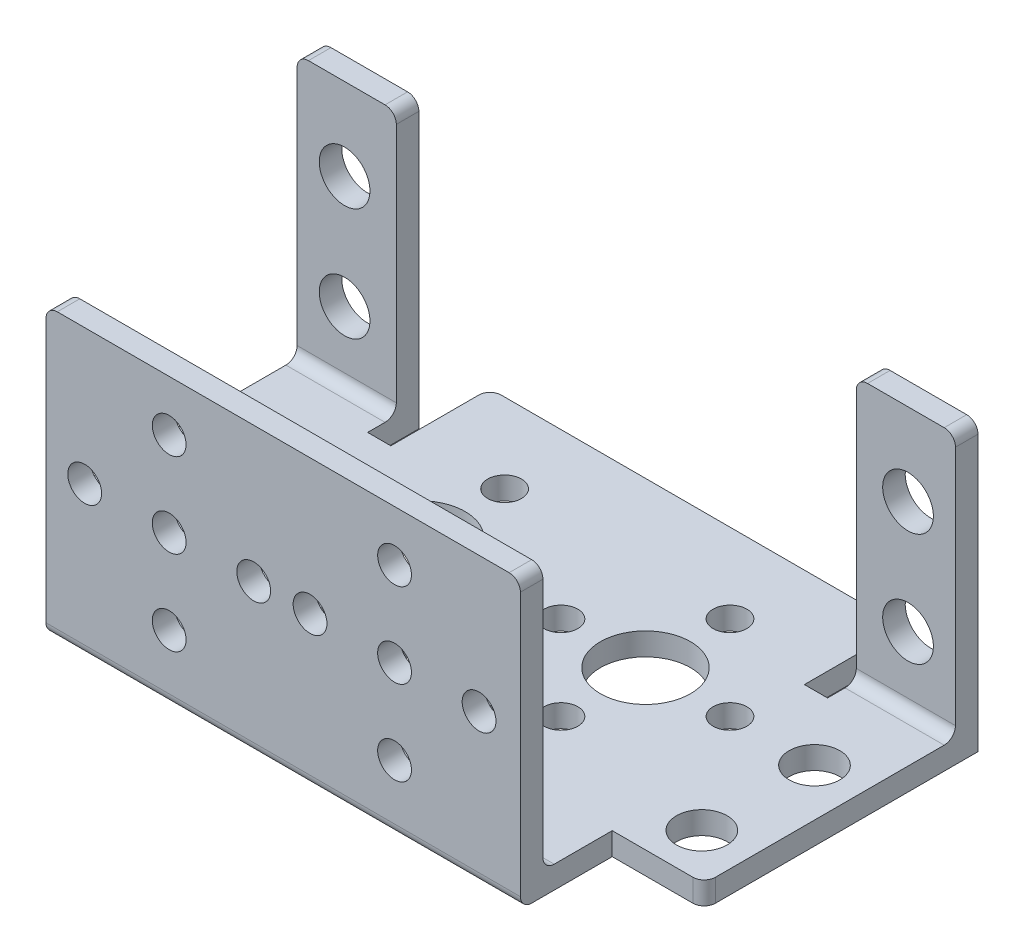
SolidWorks part; units mm, degrees
material "1060 Alloy"
ref_plane "Front Plane" through (0, 0, 0) normal (0, 0, 1) x (1, 0, 0)
ref_plane "Top Plane" through (0, 0, 0) normal (0, 1, 0) x (1, 0, 0)
ref_plane "Right Plane" through (0, 0, 0) normal (1, 0, 0) x (0, 0, -1)
sketch "Sketch2" plane through (0, 0, 0) normal (0, 0, 1) x (1, 0, 0)
  line L1 (0, 0) -> (58.42, 0)
  line L2 (0, 0) -> (0, 25.4)
  line L3 (0, 25.4) -> (58.42, 25.4)
  line L4 (58.42, 0) -> (58.42, 25.4)
  dimension "D1" = 25.4
  dimension "D2" = 58.42
extrude "Boss-Extrude1" add sketch "Sketch2" along normal blind 36.7
sketch "Sketch3" plane through (58.42, 0, 0) normal (1, 0, 0) x (0, 0, -1)
  line L0 (-36.7, 25.4) -> (0, 25.4) construction
  line L1 (-34.7, 25.4) -> (-6.252, 25.4)
  line L2 (-34.7, 25.4) -> (-34.7, 2)
  line L3 (-34.7, 2) -> (-6.252, 2)
  line L4 (-6.252, 25.4) -> (-6.252, 2)
  line L5 (-36.7, 0) -> (-36.7, 25.4) construction
  line L6 (-36.7, 0) -> (0, 0) construction
  line L7 (-4.252, 25.4) -> (-4.252, 2)
  line L8 (-4.252, 2) -> (0, 2)
  line L9 (0, 0) -> (0, 25.4) construction
  line L10 (-6.252, 25.4) -> (-4.252, 25.4)
  line M1 (0, 0) -> (0, 25.4)
  line M2 (0, 25.4) -> (-36.7, 25.4)
  dimension "D1" = 2
  dimension "D2" = 2
  dimension "D3" = 28.448
  dimension "D4" = 2
extrude "Cut-Extrude1" cut sketch "Sketch3" against normal up to next contours L7 L8 M1 M2 | L4 L2 L3 M2
sketch "Sketch4" plane through (0, 0, 36.7) normal (0, 0, 1) x (1, 0, 0)
  line L0 (0, 25.4) -> (58.42, 0) construction
  line L1 (58.42, 25.4) -> (0, 0) construction
  line L2 (58.42, 25.4) -> (0, 25.4) construction
  line L3 (50.26, 0) -> (8.16, 0)
  line L4 (50.26, 0) -> (50.26, 25.4)
  line L5 (50.26, 25.4) -> (8.16, 25.4)
  line L6 (8.16, 0) -> (8.16, 25.4)
  line L7 (50.26, 0) -> (8.16, 25.4) construction
  line L8 (50.26, 25.4) -> (8.16, 0) construction
  line L9 (0, 2) -> (58.42, 2)
  line L10 (8.16, 25.4) -> (0, 25.4)
  line L11 (8.16, 25.4) -> (8.16, 0)
  line L12 (8.16, 0) -> (0, 0)
  line L13 (0, 25.4) -> (0, 0)
  line L14 (50.26, 25.4) -> (58.42, 25.4)
  line L15 (50.26, 25.4) -> (50.26, 0)
  line L16 (50.26, 0) -> (58.42, 0)
  line L17 (58.42, 25.4) -> (58.42, 0)
  point P8 (29.21, 12.7)
  line M5 (0, 25.4) -> (0, 0)
  line M7 (58.42, 0) -> (58.42, 25.4)
  line M8 (58.42, 25.4) -> (0, 25.4)
  dimension "D1" = 42.1
  dimension "D2" = 2
extrude "Cut-Extrude3" cut sketch "Sketch4" against normal blind 2 contours L9 L6 M5 M8 | L4 L9 M7 M8
fillet "Fillet1" radius 1 4 edges at (29.21, 0, 36.7) (8.16, 25.4, 35.7) (50.26, 25.4, 35.7) (29.21, 2, 34.7)
sketch "Sketch5" plane through (0, 0, 4.252) normal (0, 0, -1) x (-1, 0, 0)
  line L0 (0, 2) -> (-58.42, 2) construction
  line L1 (-58.42, 25.4) -> (-49.62, 25.4)
  line L2 (-58.42, 25.4) -> (-58.42, 2)
  line L3 (-58.42, 2) -> (-49.62, 2)
  line L4 (-49.62, 25.4) -> (-49.62, 2)
  line L5 (0, 25.4) -> (-58.42, 25.4) construction
  line L6 (0, 25.4) -> (-8.8, 25.4)
  line L7 (0, 25.4) -> (0, 2)
  line L8 (0, 2) -> (-8.8, 2)
  line L9 (-8.8, 25.4) -> (-8.8, 2)
  line L10 (0, 2) -> (0, 25.4) construction
  line L12 (-49.62, 25.4) -> (-8.8, 25.4)
  line L13 (-49.62, 25.4) -> (-49.62, 2)
  line L14 (-49.62, 2) -> (-8.8, 2)
  line L15 (-8.8, 25.4) -> (-8.8, 2)
  line M2 (0, 25.4) -> (-58.42, 25.4)
  line M4 (-58.42, 2) -> (0, 2)
  dimension "D1" = 8.8
  dimension "D2" = 8.8
extrude "Cut-Extrude5" cut sketch "Sketch5" against normal up to next contours L9 L4 M2 M4
sketch "Sketch6" plane through (0, 2, 0) normal (0, 1, 0) x (1, 0, 0)
  line L0 (0, 0) -> (58.42, 0) construction
  line L1 (47.56, 0) -> (10.86, 0)
  line L2 (47.56, 0) -> (47.56, -8.8)
  line L3 (47.56, -8.8) -> (10.86, -8.8)
  line L4 (10.86, 0) -> (10.86, -8.8)
  line L5 (0, 0) -> (58.42, -36.7) construction
  line L6 (58.42, -36.7) -> (0, -36.7) construction
  line L7 (0, -36.7) -> (58.42, 0) construction
  line L8 (29.21, -33.7) -> (29.21, 0) construction
  line L9 (8.16, -33.7) -> (50.26, -33.7) construction
  line L10 (47.56, -4.4) -> (10.86, -4.4) construction
  line L11 (29.21, -8.8) -> (29.21, 0) construction
  line L12 (10.86, 0) -> (0, 0)
  line L13 (49.62, -6.252) -> (47.56, -6.252)
  line L14 (49.62, -6.252) -> (49.62, -8.8)
  line L15 (49.62, -8.8) -> (47.56, -8.8)
  line L16 (47.56, -6.252) -> (47.56, -8.8)
  line L17 (8.8, -6.252) -> (10.86, -6.252)
  line L18 (8.8, -6.252) -> (8.8, -8.8)
  line L19 (8.8, -8.8) -> (10.86, -8.8)
  line L20 (10.86, -6.252) -> (10.86, -8.8)
  line L21 (0, 0) -> (0, -4.252)
  line L22 (0, -4.252) -> (8.8, -4.252)
  line L23 (8.8, -4.252) -> (8.8, -6.252)
  line L24 (47.56, 0) -> (58.42, 0)
  line L25 (58.42, 0) -> (58.42, -4.252)
  line L26 (58.42, -4.252) -> (49.62, -4.252)
  line L27 (49.62, -4.252) -> (58.42, -4.252) construction
  line L28 (49.62, -4.252) -> (49.62, -6.252)
  line M1 (0, 0) -> (0, -4.252)
  line M2 (0, -4.252) -> (8.8, -4.252)
  line M3 (8.8, -4.252) -> (8.8, -6.252)
  line M13 (49.62, -6.252) -> (49.62, -4.252)
  line M14 (49.62, -4.252) -> (58.42, -4.252)
  line M15 (58.42, -4.252) -> (58.42, 0)
  line M16 (58.42, 0) -> (0, 0)
  dimension "D1" = 8.8
  dimension "D2" = 36.7
  dimension "D3" = 0
extrude "Cut-Extrude6" cut sketch "Sketch6" against normal blind 2 contours L17 L4 M3 M16 M1 M2 | L13 L2 M13 M14 M15 M16 | L15 L14 L13 L2 | L18 L19 L4 L17
sketch "Sketch7" plane through (0, 2, 0) normal (0, 1, 0) x (1, 0, 0)
  line L0 (29.21, 0) -> (29.21, -46.2253) construction
  line L1 (58.42, -6.252) -> (50.26, -6.252)
  line L2 (58.42, -6.252) -> (58.42, -28.552)
  line L3 (58.42, -28.552) -> (50.26, -28.552)
  line L4 (50.26, -6.252) -> (50.26, -28.552)
  line L5 (10.86, 0) -> (47.56, 0) construction
  line L6 (8.16, -36.7) -> (0, -36.7)
  line L7 (50.26, -28.552) -> (58.42, -28.552)
  line L8 (50.26, -28.552) -> (50.26, -36.7)
  line L9 (50.26, -36.7) -> (58.42, -36.7)
  line L10 (58.42, -28.552) -> (58.42, -36.7)
  line L11 (0, -28.552) -> (0, -36.7)
  line L12 (0, -28.552) -> (8.16, -28.552)
  line L13 (8.16, -28.552) -> (8.16, -36.7)
  line M4 (0, -6.252) -> (0, -36.7)
  line M5 (0, -36.7) -> (8.16, -36.7)
  line M6 (8.16, -36.7) -> (8.16, -33.7)
  line M8 (50.26, -33.7) -> (50.26, -36.7)
  line M9 (50.26, -36.7) -> (58.42, -36.7)
  line M10 (58.42, -36.7) -> (58.42, -6.252)
  dimension "D1" = 22.3
extrude "Cut-Extrude7" cut sketch "Sketch7" against normal blind 2 contours L13 L12 M4 M5 M6 | L3 L8 M8 M9 M10
fillet "Fillet2" radius 1 8 edges at (0, 1, 28.552) (58.42, 1, 28.552) (47.56, 1, 0) (58.42, 25.4, 5.252) (49.62, 25.4, 5.252) (8.8, 25.4, 5.252) (0, 25.4, 5.252) (10.86, 1, 0)
sketch "Sketch8" plane through (0, 0, 36.7) normal (0, 0, 1) x (1, 0, 0)
  line L0 (7.9231, 13.4) -> (50.26, 13.4) construction
  line L1 (50.26, 1) -> (50.26, 24.4) construction
  line L2 (49.26, 25.4) -> (9.16, 25.4) construction
  line L3 (29.21, 25.4) -> (29.21, 1) construction
  line L4 (8.16, 1) -> (50.26, 1) construction
  line L6 (39.0916, 5.9) -> (19.0916, 5.9) construction
  line L7 (39.0916, 5.9) -> (39.0916, 20.9) construction
  line L8 (39.0916, 20.9) -> (19.0916, 20.9) construction
  line L9 (19.0916, 5.9) -> (19.0916, 20.9) construction
  line L10 (39.0916, 5.9) -> (19.0916, 20.9) construction
  line L11 (39.0916, 20.9) -> (19.0916, 5.9) construction
  circle A0 centre (19.0916, 13.4) radius 1.5
  circle A1 centre (19.0916, 20.9) radius 1.5
  circle A2 centre (26.5916, 13.4) radius 1.5
  circle A3 centre (19.0916, 5.9) radius 1.5
  circle A4 centre (11.5916, 13.4) radius 1.5
  circle A5 centre (39.0916, 13.4) radius 1.5
  circle A6 centre (39.0916, 13.4) radius 7.5 construction
  circle A7 centre (39.0916, 5.9) radius 1.5
  circle A8 centre (31.5916, 13.4) radius 1.5
  circle A9 centre (39.0916, 20.9) radius 1.5
  circle A10 centre (46.5916, 13.4) radius 1.5
  point P10 (29.0916, 13.4)
  point P27 (19.0916, 13.4)
  point P38 (39.0916, 13.4)
  dimension "D4" = 3
  dimension "D5" = 3
  dimension "D7" = 3
  dimension "D8" = 3
  dimension "D1" = 12
  dimension "D2" = 15
  dimension "D3" = 20
  dimension "D6" = 4
  dimension "D9" = 4
extrude "Cut-Extrude8" cut sketch "Sketch8" against normal blind 2
sketch "Sketch9" plane through (0, 2, 0) normal (0, 1, 0) x (1, 0, 0)
  line L0 (1, -28.552) -> (53.84, -28.552) construction
  line L1 (57.42, -28.552) -> (50.26, -28.552) construction
  line L3 (19.21, -22.052) -> (39.21, -22.052) construction
  line L4 (7.8, -6.252) -> (1, -6.252) construction
  line L5 (4.21, -14.552) -> (54.21, -14.552) construction
  line L6 (4.21, -14.552) -> (4.21, -24.552) construction
  line L7 (4.21, -24.552) -> (54.21, -24.552) construction
  line L8 (54.21, -14.552) -> (54.21, -24.552) construction
  line L9 (4.21, -14.552) -> (54.21, -24.552) construction
  line L10 (4.21, -24.552) -> (54.21, -14.552) construction
  line L11 (1, -6.252) -> (4.4, -6.252) construction
  line L12 (4.21, -14.552) -> (29.21, -24.552) construction
  line L13 (29.21, -14.552) -> (4.21, -24.552) construction
  line L14 (19.21, -22.052) -> (19.21, -7.052) construction
  line L15 (19.21, -7.052) -> (39.21, -7.052) construction
  line L16 (29.21, -14.552) -> (54.21, -24.552) construction
  line L17 (54.21, -24.552) -> (54.21, -14.552) construction
  line L18 (54.21, -14.552) -> (29.21, -24.552) construction
  line L19 (39.21, -22.052) -> (39.21, -7.052) construction
  line L20 (19.21, -22.052) -> (39.21, -7.052) construction
  line L21 (19.21, -7.052) -> (39.21, -22.052) construction
  circle A0 centre (4.21, -14.552) radius 2.25
  circle A1 centre (4.21, -24.552) radius 2.25
  circle A2 centre (54.21, -14.552) radius 2.25
  circle A3 centre (54.21, -24.552) radius 2.25
  circle A4 centre (29.21, -24.552) radius 4
  circle A5 centre (29.21, -24.552) radius 7.5 construction
  circle A6 centre (29.21, -17.052) radius 1.5
  circle A7 centre (36.71, -24.552) radius 1.5
  circle A8 centre (29.21, -32.052) radius 1.5
  circle A9 centre (21.71, -24.552) radius 1.5
  circle A10 centre (39.21, -14.552) radius 4
  circle A11 centre (19.21, -14.552) radius 4
  circle A14 centre (39.21, -14.552) radius 7.5 construction
  circle A15 centre (31.71, -14.552) radius 1.5
  circle A16 centre (39.21, -7.052) radius 1.5
  circle A17 centre (46.71, -14.552) radius 1.5
  circle A18 centre (39.21, -22.052) radius 1.5
  circle A19 centre (19.21, -14.552) radius 7.5 construction
  circle A20 centre (26.71, -14.552) radius 1.5
  circle A21 centre (19.21, -22.052) radius 1.5
  circle A22 centre (11.71, -14.552) radius 1.5
  circle A23 centre (19.21, -7.052) radius 1.5
  point P9 (29.21, -19.552)
  point P40 (29.21, -25.452)
  point P41 (29.21, -25.452)
  point P42 (29.21, -24.552)
  point P58 (39.21, -14.552)
  point P68 (19.21, -14.552)
  dimension "D3" = 4.5
  dimension "D4" = 4.5
  dimension "D5" = 4.5
  dimension "D6" = 4.5
  dimension "D7" = 8
  dimension "D8" = 8
  dimension "D9" = 15
  dimension "D10" = 3
  dimension "D14" = 8
  dimension "D15" = 8
  dimension "D16" = 15
  dimension "D17" = 3
  dimension "D18" = 4
  dimension "D19" = 3
  dimension "D1" = 10
  dimension "D2" = 50
  dimension "D11" = 4
  dimension "D12" = 15
  dimension "D13" = 20
  dimension "D20" = 4
extrude "Cut-Extrude9" cut sketch "Sketch9" against normal blind 2
sketch "Sketch10" plane through (0, 0, 4.252) normal (0, 0, -1) x (-1, 0, 0)
  line L0 (-54.02, 25.4) -> (-54.02, 0) construction
  line L1 (-50.62, 25.4) -> (-57.42, 25.4) construction
  line L2 (-49.62, 0) -> (-58.42, 0) construction
  line L3 (-4.4, 25.4) -> (-4.4, 0) construction
  line L4 (-1, 25.4) -> (-7.8, 25.4) construction
  line L5 (0, 0) -> (-8.8, 0) construction
  line L6 (-54.02, 18.11) -> (-4.4, 8.11) construction
  line L7 (-54.02, 18.11) -> (-4.4, 18.11) construction
  line L8 (-54.02, 18.11) -> (-54.02, 8.11) construction
  line L9 (-54.02, 8.11) -> (-4.4, 8.11) construction
  line L10 (-4.4, 18.11) -> (-4.4, 8.11) construction
  line L11 (-4.4, 8.11) -> (-4.4, 18.11) construction
  line L12 (-4.4, 18.11) -> (-54.02, 8.11) construction
  line L14 (-4.21, 8.11) -> (-54.21, 8.11) construction
  line L15 (-4.21, 8.11) -> (-4.21, 18.11)
  line L16 (-4.21, 18.11) -> (-54.21, 18.11) construction
  line L17 (-54.21, 8.11) -> (-54.21, 18.11)
  line L18 (-4.21, 8.11) -> (-54.21, 18.11) construction
  line L19 (-4.21, 18.11) -> (-54.21, 8.11) construction
  circle A0 centre (-4.21, 18.11) radius 2.25
  circle A1 centre (-54.21, 18.11) radius 2.25
  circle A2 centre (-54.21, 8.11) radius 2.25
  circle A3 centre (-4.21, 8.11) radius 2.25
  point P16 (-29.21, 13.11)
  dimension "D3" = 4.5
  dimension "D1" = 10
  dimension "D2" = 50
  dimension "D6" = 8.11
  dimension "D4" = 2
  dimension "D5" = 2
extrude "Cut-Extrude10" cut sketch "Sketch10" against normal blind 2
fillet "Fillet3" radius 1 2 edges at (4.4, 2, 6.252) (54.02, 2, 6.252)
